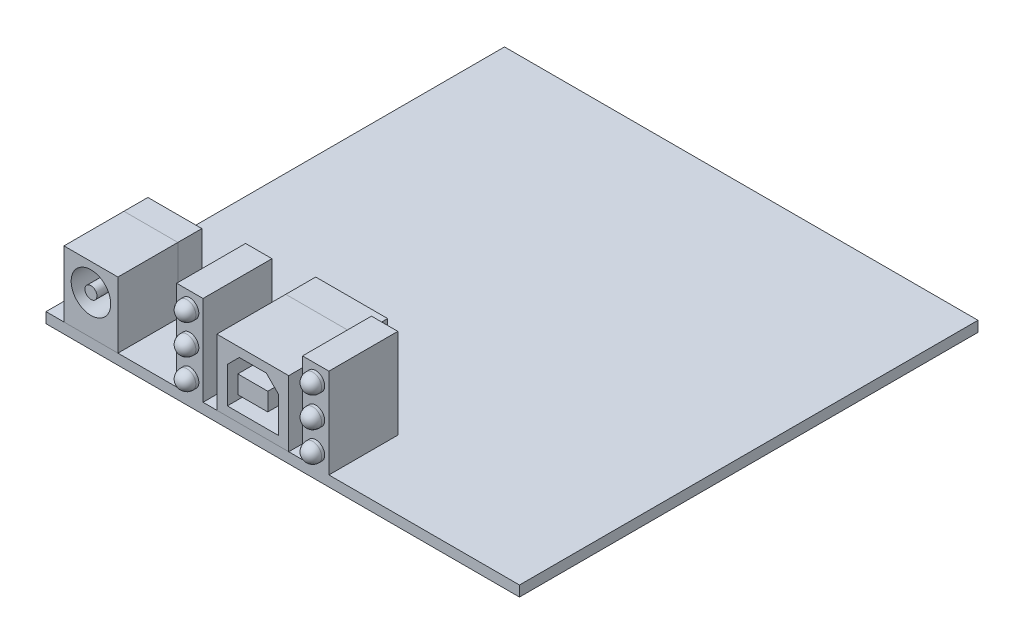
SolidWorks part; units mm, degrees
ref_plane "Front Plane" through (0, 0, 0) normal (0, 0, 1) x (1, 0, 0)
ref_plane "Top Plane" through (0, 0, 0) normal (0, 1, 0) x (1, 0, 0)
ref_plane "Right Plane" through (0, 0, 0) normal (1, 0, 0) x (0, 0, -1)
sketch "Sketch1" plane through (0, 0, 0) normal (0, 1, 0) x (1, 0, 0)
  line L1 (-39.5, 38.25) -> (39.5, 38.25)
  line L2 (-39.5, 38.25) -> (-39.5, -38.25)
  line L3 (-39.5, -38.25) -> (39.5, -38.25)
  line L4 (39.5, 38.25) -> (39.5, -38.25)
  line L5 (-39.5, 38.25) -> (39.5, -38.25) construction
  line L6 (-39.5, -38.25) -> (39.5, 38.25) construction
  point P0 (0, 0)
  dimension "D1" = 79
  dimension "D2" = 76.5
extrude "Boss-Extrude1" add sketch "Sketch1" along normal blind 1.75
sketch "Sketch2" plane through (0, 0, 38.25) normal (0, 0, 1) x (1, 0, 0)
  line L0 (-32, 0) -> (-32, 14.5) construction
  line L1 (-39.5, 0) -> (39.5, 0) construction
  line L2 (-39.5, 1.75) -> (-39.5, 0) construction
  line L3 (-39.5, 1.75) -> (39.5, 1.75) construction
  line L5 (-27.5, 12.75) -> (-36.5, 12.75)
  line L6 (-27.5, 12.75) -> (-27.5, 1.75)
  line L7 (-27.5, 1.75) -> (-36.5, 1.75)
  line L8 (-36.5, 12.75) -> (-36.5, 1.75)
  line L9 (-27.5, 12.75) -> (-36.5, 1.75) construction
  line L10 (-27.5, 1.75) -> (-36.5, 12.75) construction
  circle A0 centre (-32, 8.25) radius 3.3
  circle A2 centre (-32, 8.25) radius 1
  point P10 (-32, 7.25)
  line M6 (39.5, 1.75) -> (-39.5, 1.75)
  dimension "D3" = 6.6
  dimension "D6" = 2
  dimension "D1" = 7.5
  dimension "D2" = 6.5
  dimension "D4" = 9
  dimension "D5" = 11
extrude "Boss-Extrude2" add sketch "Sketch2" against normal blind 10 separate body contours L5 L8 L6 A0 M6 | A2
sketch "Sketch3" plane through (0, 0, 28.25) normal (0, 0, -1) x (-1, 0, 0)
  line L0 (-39.5, 1.75) -> (39.5, 1.75) construction
  line L1 (36.5, 12.75) -> (36.5, 1.75) construction
  line L2 (27.5, 12.75) -> (27.5, 1.75) construction
  line L3 (27.5, 12.75) -> (36.5, 12.75) construction
  line L4 (27.5, 1.75) -> (36.5, 1.75)
  line L5 (36.5, 12.75) -> (36.5, 1.75)
  line L6 (27.5, 12.75) -> (27.5, 1.75)
  line L7 (27.5, 12.75) -> (36.5, 12.75)
extrude "Boss-Extrude3" add sketch "Sketch3" along normal blind 4
sketch "Sketch4" plane through (0, 0, 38.25) normal (0, 0, 1) x (1, 0, 0)
  line L0 (-15.5, 1.75) -> (-15.5, 23.4028) construction
  line L1 (-39.5, 1.75) -> (39.5, 1.75) construction
  line L2 (-39.5, 1.75) -> (-39.5, 0) construction
  line L3 (5.5, 1.75) -> (5.5, 24.9746) construction
  line L4 (-5, 1.75) -> (-5, 21.1574) construction
  line L5 (-17.7, 16.75) -> (-13.3, 16.75)
  line L6 (-17.7, 16.75) -> (-17.7, 1.75)
  line L7 (-17.7, 1.75) -> (-13.3, 1.75)
  line L8 (-13.3, 16.75) -> (-13.3, 1.75)
  line L9 (-17.7, 16.75) -> (-13.3, 1.75) construction
  line L10 (-17.7, 1.75) -> (-13.3, 16.75) construction
  line L11 (3.3, 16.75) -> (7.7, 16.75)
  line L12 (3.3, 16.75) -> (3.3, 1.75)
  line L13 (3.3, 1.75) -> (7.7, 1.75)
  line L14 (7.7, 16.75) -> (7.7, 1.75)
  line L15 (3.3, 16.75) -> (7.7, 1.75) construction
  line L16 (3.3, 1.75) -> (7.7, 16.75) construction
  line L17 (-9.25, 9.25) -> (-7.25, 11.25)
  line L18 (-11, 12.75) -> (1, 12.75)
  line L19 (-11, 12.75) -> (-11, 1.75)
  line L20 (-11, 1.75) -> (1, 1.75)
  line L21 (1, 12.75) -> (1, 1.75)
  line L22 (-11, 12.75) -> (1, 1.75) construction
  line L23 (-11, 1.75) -> (1, 12.75) construction
  line L24 (-7.25, 11.25) -> (-2.75, 11.25)
  line L25 (-9.25, 9.25) -> (-9.25, 3.25)
  line L26 (-9.25, 3.25) -> (-0.75, 3.25)
  line L27 (-0.75, 9.25) -> (-0.75, 3.25)
  line L28 (-9.25, 11.25) -> (-0.75, 3.25) construction
  line L29 (-9.25, 3.25) -> (-0.75, 11.25) construction
  line L30 (-2.75, 11.25) -> (-0.75, 9.25)
  line L32 (-7.5, 8.75) -> (-2.5, 8.75)
  line L33 (-7.5, 8.75) -> (-7.5, 5.75)
  line L34 (-7.5, 5.75) -> (-2.5, 5.75)
  line L35 (-2.5, 8.75) -> (-2.5, 5.75)
  line L36 (-7.5, 8.75) -> (-2.5, 5.75) construction
  line L37 (-7.5, 5.75) -> (-2.5, 8.75) construction
  point P8 (-15.5, 9.25)
  point P13 (5.5, 9.25)
  point P20 (-5, 7.25)
  point P25 (-5, 7.25)
  point P34 (-5, 7.25)
  line M24 (39.5, 1.75) -> (-39.5, 1.75)
  dimension "D1" = 24
  dimension "D2" = 21
  dimension "D3" = 4.4
  dimension "D4" = 15
  dimension "D5" = 4.4
  dimension "D6" = 15
  dimension "D7" = 10.5
  dimension "D8" = 12
  dimension "D9" = 11
  dimension "D10" = 8.5
  dimension "D11" = 8
  dimension "D12" = 5
  dimension "D13" = 3
extrude "Boss-Extrude4" add sketch "Sketch4" against normal blind 11.5 separate body contours L21 L18 L19 L24 L30 L27 L26 L25 L17 M24 | L8 L5 L6 M24 | L14 L11 L12 M24 | L33 L34 L35 L32
sketch "Sketch5" plane through (0, 0, 26.75) normal (0, 0, -1) x (-1, 0, 0)
  line L1 (-1, 12.75) -> (11, 12.75)
  line L2 (-1, 12.75) -> (-1, 1.75)
  line L3 (-1, 1.75) -> (11, 1.75)
  line L4 (11, 12.75) -> (11, 1.75)
extrude "Boss-Extrude5" add sketch "Sketch5" along normal blind 5 separate body
sketch "Sketch6" plane through (0, 0, 38.25) normal (0, 0, 1) x (1, 0, 0)
  line L0 (-15.5, 1.75) -> (-15.5, 16.75) construction
  line L1 (-13.3, 1.75) -> (-17.7, 1.75) construction
  line L2 (-17.7, 16.75) -> (-13.3, 16.75) construction
  line L3 (5.5, 1.75) -> (5.5, 16.75) construction
  line L4 (7.7, 1.75) -> (3.3, 1.75) construction
  line L5 (3.3, 16.75) -> (7.7, 16.75) construction
  circle A0 centre (-15.5, 9.25) radius 1.5
  circle A1 centre (5.5, 9.25) radius 1.5
  circle A2 centre (-15.5, 4.25) radius 1.5
  circle A3 centre (5.5, 4.25) radius 1.5
  circle A4 centre (-15.5, 14.25) radius 1.5
  circle A5 centre (5.5, 14.25) radius 1.5
  circle A8 centre (-15.5, 19.25) radius 1.5 [skipped]
  circle A9 centre (5.5, 19.25) radius 1.5 [skipped]
  dimension "D1" = 3
  dimension "D2" = 3
  dimension "D3" = 2
  dimension "D4" = 2
extrude "Boss-Extrude6" add sketch "Sketch6" along normal blind 2
fillet "Fillet1" radius 1.5 6 edges at (-14, 9.25, 40.25) (-14, 14.25, 40.25) (7, 4.25, 40.25) (7, 9.25, 40.25) (7, 14.25, 40.25) (-14, 4.25, 40.25)
